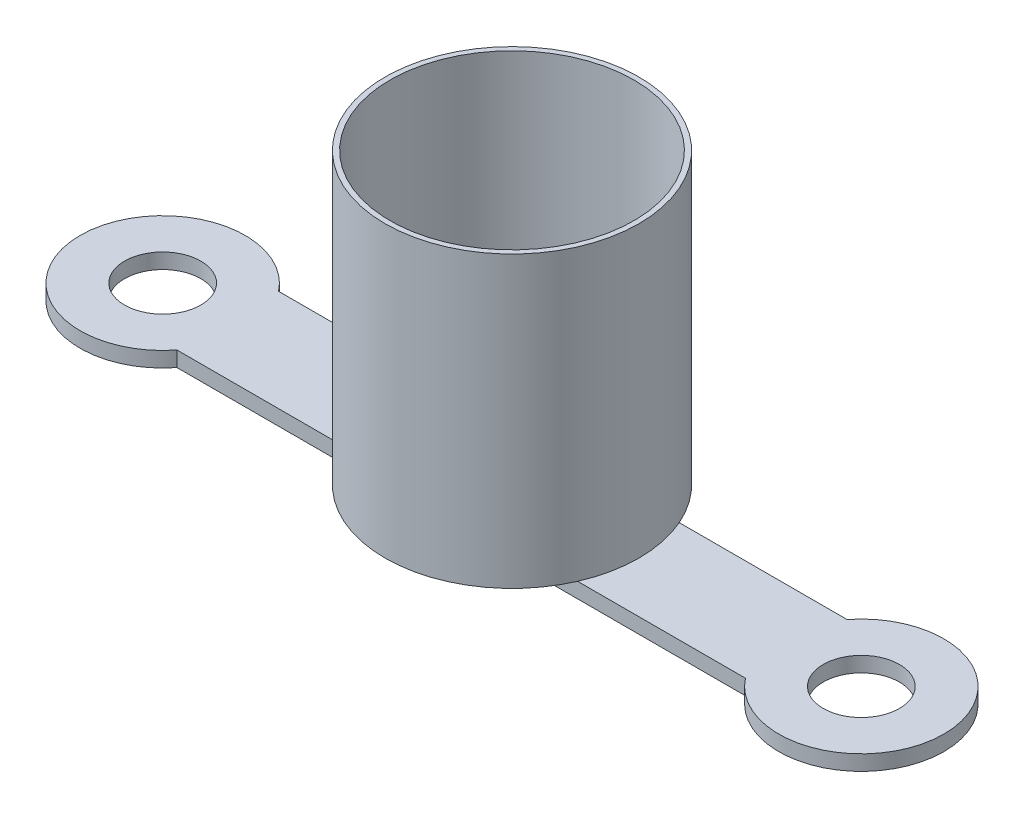
SolidWorks part; units mm, degrees
ref_plane "Piano frontale" through (0, 0, 0) normal (0, 0, 1) x (1, 0, 0)
ref_plane "Piano superiore" through (0, 0, 0) normal (0, 1, 0) x (1, 0, 0)
ref_plane "Piano destro" through (0, 0, 0) normal (1, 0, 0) x (0, 0, -1)
sketch "Schizzo1" plane through (0, 0, 0) normal (0, 1, 0) x (1, 0, 0)
  line L0 (2.5617, -2) -> (24.9383, -2)
  line L1 (24.9383, -2) -> (24.9383, 2)
  line L2 (24.9383, 2) -> (2.5617, 2)
  line L3 (2.5617, 2) -> (2.5617, -2)
  circle A0 centre (0, 0) radius 3.25
  circle A1 centre (27.5, 0) radius 3.25
  circle A2 centre (0, 0) radius 1.5
  circle A3 centre (27.5, 0) radius 1.5
  point P10 (0, 0)
  dimension "D1" = 6.5
  dimension "D2" = 6.5
  dimension "D3" = 3
  dimension "D4" = 3
  dimension "D5" = 4
  dimension "D6" = 27.5
extrude "Estrusione-Estrusione1" add sketch "Schizzo1" along normal blind 0.6 contours L3 A0 A2 | A1 L2 A0 L0 | L3 A0 | L1 A1 A3 | L1 A1
sketch "Schizzo2" plane through (0, 0.6, 0) normal (0, 1, 0) x (1, 0, 0)
  circle A0 centre (13.75, 0) radius 5
  dimension "D1" = 13.75
  dimension "D2" = 10
extrude "Estrusione-Estrusione2" add sketch "Schizzo2" along normal blind 0.6
sketch "Schizzo3" plane through (0, 1.2, 0) normal (0, 1, 0) x (1, 0, 0)
  circle A0 centre (13.75, 0) radius 5
  circle A1 centre (13.75, 0) radius 5 construction
  circle A2 centre (13.75, 0) radius 4.8
  dimension "D1" = 0.2
extrude "Estrusione-Estrusione3" add sketch "Schizzo3" along normal blind 10.8
